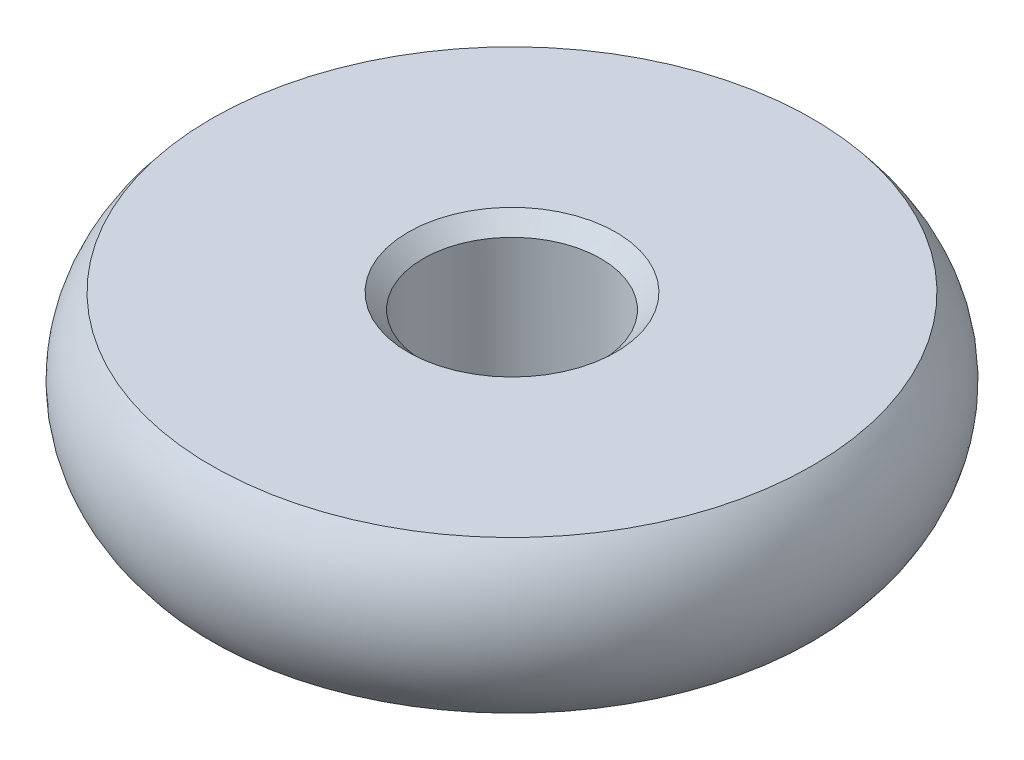
SolidWorks part; units mm, degrees
material "Custom Plastic"
ref_plane "Front Plane" through (0, 0, 0) normal (0, 0, 1) x (1, 0, 0)
ref_plane "Top Plane" through (0, 0, 0) normal (0, 1, 0) x (1, 0, 0)
ref_plane "Right Plane" through (0, 0, 0) normal (1, 0, 0) x (0, 0, -1)
sketch "Sketch1" plane through (0, 0, 0) normal (0, 0, 1) x (1, 0, 0)
  line L0 (0, -1000) -> (0, 49000) construction
  line L1 (-1000, 0) -> (49000, 0) construction
  line L2 (17.5, 15) -> (59.2705, 15)
  line L3 (17.5, -15) -> (59.2705, -15)
  line L4 (17.5, 15) -> (17.5, -15)
  arc A1 (59.2705, -15) -> (59.2705, 15) centre (42.5, 0) ccw
  point P5 (65, 0)
  dimension "D1" = 22.5
  dimension "D2" = 130
  dimension "D3" = 30
  dimension "D4" = 17.5
revolve "Revolve1" add sketch "Sketch1" angle 360 about L0
chamfer "Chamfer1" distance 3 angle 45 2 edges at (17.5, 15, 0) (17.5, -15, 0)
